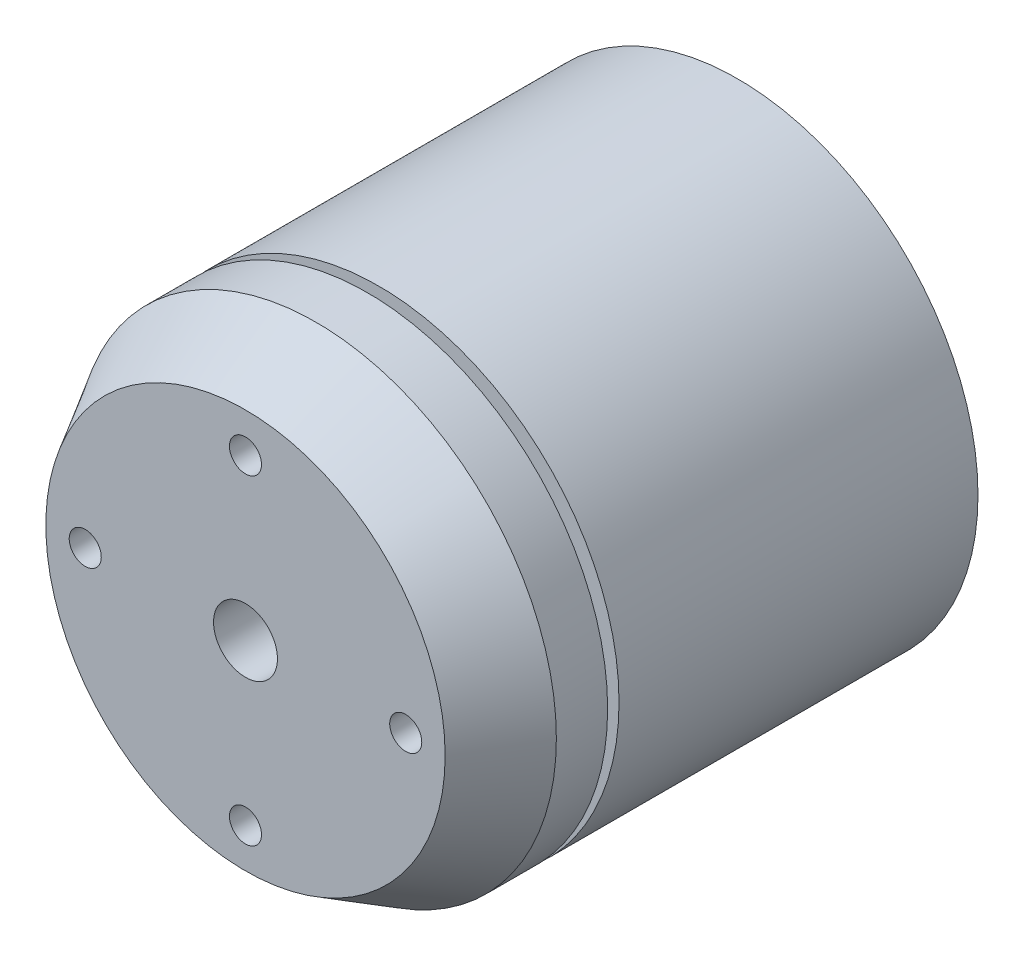
SolidWorks part; units mm, degrees
ref_plane "Front Plane" through (0, 0, 0) normal (0, 0, 1) x (1, 0, 0)
ref_plane "Top Plane" through (0, 0, 0) normal (0, 1, 0) x (1, 0, 0)
ref_plane "Right Plane" through (0, 0, 0) normal (1, 0, 0) x (0, 0, -1)
sketch "Sketch1" plane through (0, 0, 0) normal (1, 0, 0) x (0, 0, -1)
  line L0 (0, 0) -> (70.923, 0) construction
  line L1 (0, 0) -> (0, 15.5746)
  line L2 (0, 15.5746) -> (5.5, 18.75)
  line L3 (5.5, 18.75) -> (9.5, 18.75)
  line L4 (9.5, 18.75) -> (9.5, 14.2875)
  line L6 (10.389, 14.2875) -> (10.389, 18.75)
  line L7 (10.389, 18.75) -> (38.389, 18.75)
  line L8 (38.389, 18.75) -> (39.75, 6)
  line L9 (39.75, 6) -> (45.75, 6)
  line L10 (45.75, 6) -> (45.75, 2.49)
  line L11 (45.75, 2.49) -> (54.75, 2.49) construction
  line L12 (54.75, 2.49) -> (54.75, 0) construction
  line L13 (54.75, 0) -> (0, 0)
  line L14 (45.75, 2.49) -> (45.75, 0)
  line L15 (9.5, 14.2875) -> (10.389, 14.2875)
  dimension "D2" = 37.5
  dimension "D3" = 2.49
  dimension "D4" = 9
  dimension "D5" = 12
  dimension "D6" = 45.75
  dimension "D7" = 28
  dimension "D8" = 9.5
  dimension "D9" = 30
  dimension "D10" = 4
  dimension "D11" = 6
  dimension "D12" = 28.575
  dimension "D13" = 0.889
revolve "Revolve1" add sketch "Sketch1" angle 360 about L0
hole_wizard "M3x0.5 Tapped Hole1" positions "Sketch4" profile "Sketch3" tap size "M3x0.5" standard "ANSI Metric"
sketch "Sketch4" plane through (0, 0, 0) normal (0, 0, 1) x (1, 0, 0)
  circle A0 centre (0, 0) radius 12.5
  point P0 (0, 12.5)
  point P2 (12.5, 0)
  point P4 (-12.5, 0)
  point P6 (0, -12.5)
  dimension "D1" = 25
sketch "Sketch3" plane through (0, 12.5, 0) normal (1, 0, 0) x (0, -1, 0)
  line L0 (0, 0) -> (0, 8.3711)
  line L1 (0, 8.3711) -> (1.25, 7.62)
  line L2 (1.25, 7.62) -> (1.25, 0)
  line L5 (1.25, 0) -> (0, 0)
  line L10 (0, 8.3711) -> (-1.25, 7.62) construction
  line L11 (0, -6.35) -> (0, 107.95) construction
  dimension "Tap Drill Dia." = 2.5
  dimension "Tap Drill Depth" = 7.62
  dimension "Drill Angle" = 118
cosmetic thread "Hole Thread5" parameters "D1"=6.096, "D2"=3
cosmetic thread "Hole Thread6" parameters "D1"=6.096, "D2"=3
cosmetic thread "Hole Thread7" parameters "D1"=6.096, "D2"=3
cosmetic thread "Hole Thread8" parameters "D1"=6.096, "D2"=3
sketch "Sketch5" plane through (0, 0, 0) normal (0, 0, 1) x (1, 0, 0)
  circle A0 centre (0, 0) radius 2.493
  dimension "D1" = 4.986
extrude "Cut-Extrude1" cut sketch "Sketch5" against normal up to next
